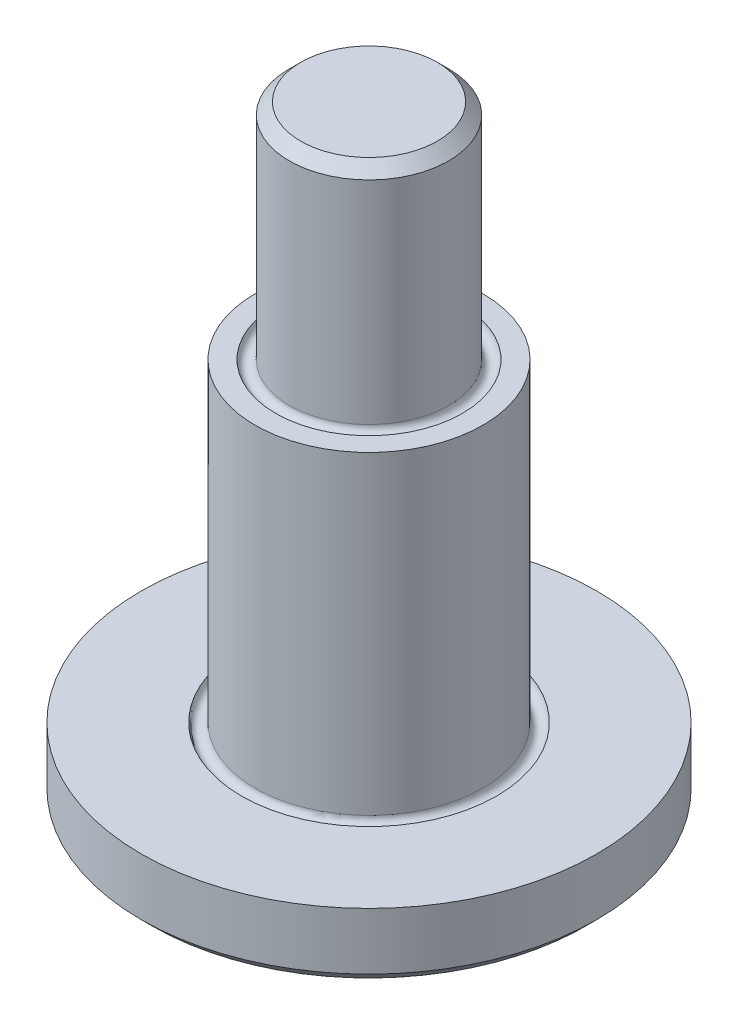
SolidWorks part; units mm, degrees
ref_plane "Plan1" through (0, 0, 0) normal (0, 0, 1) x (1, 0, 0)
ref_plane "Plan2" through (0, 0, 0) normal (0, 1, 0) x (1, 0, 0)
ref_plane "Plan3" through (0, 0, 0) normal (1, 0, 0) x (0, 0, -1)
ref_plane "Plan4" through (0, 0, 716.1319) normal (0, 0, -1) x (-1, 0, 0)
sketch "Esquisse1" plane through (0, 0, 716.1319) normal (0, 0, -1) x (-1, 0, 0)
  line L0 (-2169.9496, 588.7346) -> (-2160.4496, 588.7346)
  line L1 (-2160.4496, 588.7346) -> (-2160.4496, 615.3345)
  line L2 (-2160.4496, 615.3345) -> (-2163.4496, 615.3345)
  line L3 (-2163.4496, 615.3345) -> (-2163.9496, 614.8345)
  line L4 (-2163.9496, 614.8345) -> (-2163.9496, 605.5344)
  line L5 (-2164.5496, 605.5345) -> (-2165.4496, 605.5345)
  line L6 (-2165.4496, 605.5345) -> (-2165.4496, 591.7344)
  line L7 (-2166.0496, 591.7345) -> (-2170.4496, 591.7345)
  line L8 (-2170.4496, 591.7345) -> (-2170.4496, 589.2346)
  line L9 (-2170.4496, 589.2346) -> (-2169.9496, 588.7346)
  line L10 (-2160.4496, 588.7346) -> (-2160.4496, 615.3344) construction
  arc A0 (-2163.9496, 605.5344) -> (-2164.5496, 605.5345) centre (-2164.2496, 605.5344) cw
  arc A1 (-2165.4496, 591.7344) -> (-2166.0496, 591.7345) centre (-2165.7496, 591.7344) cw
  dimension "D4" = 0.3
  dimension "D5" = 0.3
  dimension "D8" = 10
  dimension "D1" = 13.8
  dimension "D2" = 2.9999
  dimension "D3" = 9.8
  dimension "D6" = 5
  dimension "D7" = 3.5
  dimension "D9" = 0.5
  dimension "D10" = 45
  dimension "D11" = 0.5
  dimension "D12" = 45
revolve "Base-Révolution" add sketch "Esquisse1" angle 360 about L10
